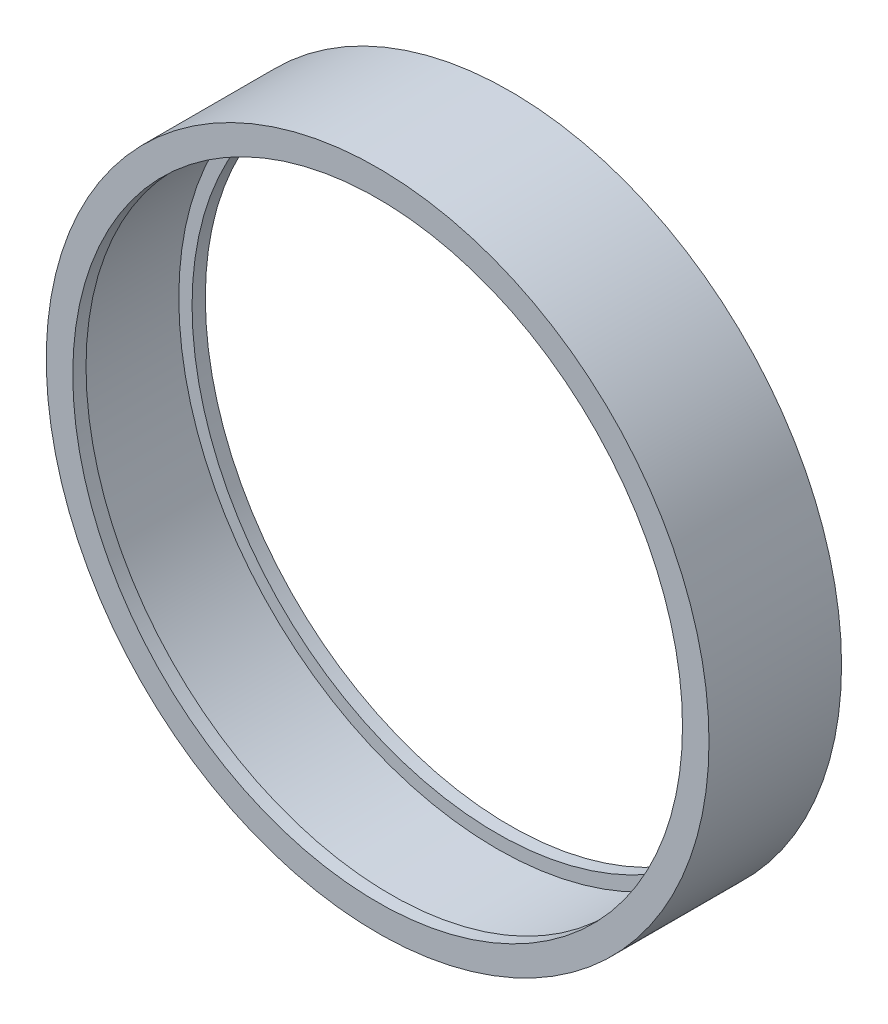
SolidWorks part; units mm, degrees
material "Plain Carbon Steel"
ref_plane "Front Plane" through (0, 0, 0) normal (0, 0, 1) x (1, 0, 0)
ref_plane "Top Plane" through (0, 0, 0) normal (0, 1, 0) x (1, 0, 0)
ref_plane "Right Plane" through (0, 0, 0) normal (1, 0, 0) x (0, 0, -1)
sketch "Sketch1" plane through (0, 0, 0) normal (0, 0, 1) x (1, 0, 0)
  circle A0 centre (0, 0) radius 50
  dimension "D1" = 100
extrude "Boss-Extrude1" add sketch "Sketch1" along normal blind 20
ref_plane "Plane2" through (0, 0, 10) normal (0, 0, -1) x (-1, 0, 0)
sketch "Sketch3" plane through (0, 0, 0) normal (0, 0, -1) x (-1, 0, 0)
  circle A0 centre (0, 0) radius 46
  circle A1 centre (0, 0) radius 46
  dimension "D1" = 92
extrude "Cut-Extrude4" cut sketch "Sketch3" against normal through all both and the other way through all contours A0
sketch "Sketch4" plane through (0, 0, 10) normal (0, 0, -1) x (-1, 0, 0)
  circle A0 centre (0, 0) radius 48
  dimension "D1" = 96
extrude "Cut-Extrude5" cut sketch "Sketch4" against normal mid plane 16
